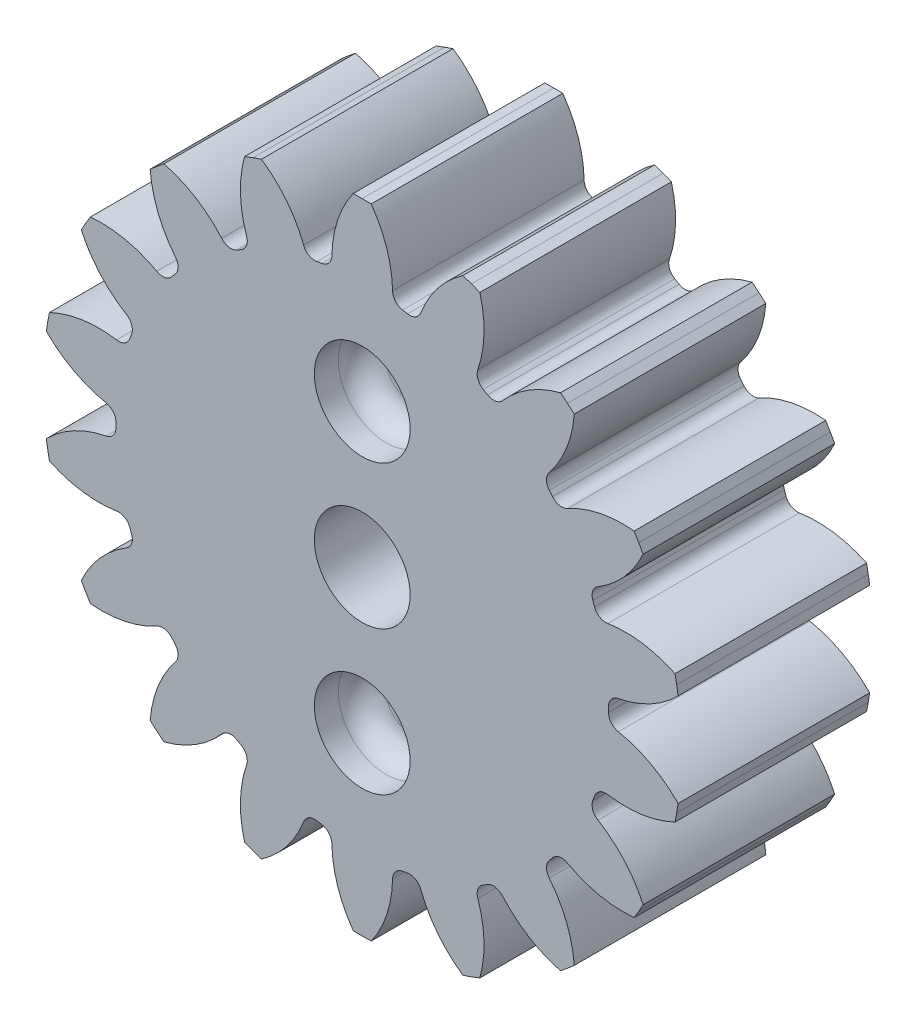
SolidWorks part; units mm, degrees
ref_plane "Front Plane" through (0, 0, 0) normal (0, 0, 1) x (1, 0, 0)
ref_plane "Top Plane" through (0, 0, 0) normal (0, 1, 0) x (1, 0, 0)
ref_plane "Right Plane" through (0, 0, 0) normal (1, 0, 0) x (0, 0, -1)
sketch "Sketch1" plane through (0, 0, 0) normal (0, 0, 1) x (1, 0, 0)
  line L0 (0, 42.3418) -> (0, -42.3418) construction
  line L1 (-42.3418, 0) -> (42.3418, 0) construction
  line L2 (0, 42.3418) -> (-1.1938, 42.325)
  line L3 (14.4817, 39.7883) -> (15.5978, 39.3642)
  line L4 (0, 42.3418) -> (1.1938, 42.325)
  line L5 (14.4817, 39.7883) -> (13.3542, 40.1808)
  line L6 (27.2168, 32.4357) -> (28.1205, 31.6554)
  line L7 (27.2168, 32.4357) -> (26.2915, 33.1902)
  line L8 (36.6691, 21.1709) -> (37.2514, 20.1286)
  line L9 (36.6691, 21.1709) -> (36.0576, 22.1963)
  line L10 (41.6985, 7.3526) -> (41.8893, 6.174)
  line L11 (41.6985, 7.3526) -> (41.4747, 8.5253)
  line L12 (41.6985, -7.3526) -> (41.4747, -8.5253)
  line L13 (41.6985, -7.3526) -> (41.8893, -6.174)
  line L14 (36.6691, -21.1709) -> (36.0576, -22.1963)
  line L15 (36.6691, -21.1709) -> (37.2514, -20.1286)
  line L16 (27.2168, -32.4357) -> (26.2915, -33.1902)
  line L17 (27.2168, -32.4357) -> (28.1205, -31.6554)
  line L18 (14.4817, -39.7883) -> (13.3542, -40.1808)
  line L19 (14.4817, -39.7883) -> (15.5978, -39.3642)
  line L20 (0, -42.3418) -> (-1.1938, -42.325)
  line L21 (0, -42.3418) -> (1.1938, -42.325)
  line L22 (-14.4817, -39.7883) -> (-15.5978, -39.3642)
  line L23 (-14.4817, -39.7883) -> (-13.3542, -40.1808)
  line L24 (-27.2168, -32.4357) -> (-28.1205, -31.6554)
  line L25 (-27.2168, -32.4357) -> (-26.2915, -33.1902)
  line L26 (-36.6691, -21.1709) -> (-37.2514, -20.1286)
  line L27 (-36.6691, -21.1709) -> (-36.0576, -22.1963)
  line L28 (-41.6985, -7.3526) -> (-41.8893, -6.174)
  line L29 (-41.6985, -7.3526) -> (-41.4747, -8.5253)
  line L30 (-41.6985, 7.3526) -> (-41.4747, 8.5253)
  line L31 (-41.6985, 7.3526) -> (-41.8893, 6.174)
  line L32 (-36.6691, 21.1709) -> (-36.0576, 22.1963)
  line L33 (-36.6691, 21.1709) -> (-37.2514, 20.1286)
  line L34 (-27.2168, 32.4357) -> (-26.2915, 33.1902)
  line L35 (-27.2168, 32.4357) -> (-28.1205, 31.6554)
  line L36 (-14.4817, 39.7883) -> (-13.3542, 40.1808)
  line L37 (-14.4817, 39.7883) -> (-15.5978, 39.3642)
  arc A0 (-36.0576, 22.1963) -> (-37.2514, 20.1286) centre (0, 0) ccw
  arc A2 (-16.0423, 28.4536) -> (-16.6204, 28.1198) centre (0, 0) ccw
  circle A3 centre (0, 0) radius 6.35
  arc A4 (4.0259, 33.778) -> (5.3431, 32.2244) centre (5.6007, 33.778) ccw
  arc A5 (-4.0259, 33.778) -> (-5.3431, 32.2244) centre (-5.6007, 33.778) cw
  arc A7 (4.0269, 33.7207) -> (1.1938, 42.325) centre (-11.211, 33.4718) ccw
  arc A8 (-4.0269, 33.7207) -> (-1.1938, 42.325) centre (11.211, 33.4718) cw
  arc A9 (7.7491, 33.0644) -> (13.3542, 40.1808) centre (21.983, 27.6188) cw
  arc A10 (7.7697, 33.1179) -> (6.0005, 32.1085) centre (6.2898, 33.6565) cw
  arc A11 (15.3172, 30.3098) -> (15.5978, 39.3642) centre (0.9131, 35.2876) ccw
  arc A12 (15.3359, 30.364) -> (16.0423, 28.4536) centre (16.8157, 29.8254) ccw
  arc A13 (18.5904, 28.42) -> (26.2915, 33.1902) centre (30.1034, 18.4346) cw
  arc A14 (18.6281, 28.4633) -> (16.6204, 28.1198) centre (17.4217, 29.4755) cw
  arc A15 (24.7601, 23.2431) -> (28.1205, 31.6554) centre (12.9271, 32.8472) ccw
  arc A16 (24.7961, 23.2877) -> (24.8065, 21.2509) centre (26.0025, 22.2754) ccw
  arc A17 (27.1895, 20.3478) -> (36.0576, 22.1963) centre (34.593, 7.0269) cw
  arc A18 (27.2397, 20.3755) -> (25.2356, 20.7395) centre (26.4523, 21.7394) cw
  arc A19 (31.2164, 13.3729) -> (37.2514, 20.1286) centre (23.3819, 26.4449) ccw
  arc A20 (31.2656, 13.4025) -> (30.5787, 11.485) centre (32.053, 12.0387) ccw
  arc A21 (32.5091, 9.8213) -> (41.4747, 8.5253) centre (34.9101, -5.2284) cw
  arc A22 (32.5658, 9.8302) -> (30.8071, 10.8576) centre (32.2923, 11.3811) cw
  arc A23 (33.9077, 1.8898) -> (41.8893, 6.174) centre (31.0165, 16.853) ccw
  arc A24 (33.964, 1.9008) -> (32.6627, 0.3338) centre (34.2374, 0.3499) ccw
  arc A25 (33.9077, -1.8898) -> (41.8893, -6.174) centre (31.0165, -16.853) cw
  arc A26 (33.964, -1.9008) -> (32.6627, -0.3338) centre (34.2374, -0.3499) cw
  arc A27 (32.5091, -9.8213) -> (41.4747, -8.5253) centre (34.9101, 5.2284) ccw
  arc A28 (32.5658, -9.8302) -> (30.8071, -10.8576) centre (32.2923, -11.3811) ccw
  arc A29 (31.2164, -13.3729) -> (37.2514, -20.1286) centre (23.3819, -26.4449) cw
  arc A30 (31.2656, -13.4025) -> (30.5787, -11.485) centre (32.053, -12.0387) cw
  arc A31 (27.1895, -20.3478) -> (36.0576, -22.1963) centre (34.593, -7.0269) ccw
  arc A32 (27.2397, -20.3755) -> (25.2356, -20.7395) centre (26.4523, -21.7394) ccw
  arc A33 (24.7601, -23.2431) -> (28.1205, -31.6554) centre (12.9271, -32.8472) cw
  arc A34 (24.7961, -23.2877) -> (24.8065, -21.2509) centre (26.0025, -22.2754) cw
  arc A35 (18.5904, -28.42) -> (26.2915, -33.1902) centre (30.1034, -18.4346) ccw
  arc A36 (18.6281, -28.4633) -> (16.6204, -28.1198) centre (17.4217, -29.4755) ccw
  arc A37 (15.3172, -30.3098) -> (15.5978, -39.3642) centre (0.9131, -35.2876) cw
  arc A38 (15.3359, -30.364) -> (16.0423, -28.4536) centre (16.8157, -29.8254) cw
  arc A39 (7.7491, -33.0644) -> (13.3542, -40.1808) centre (21.983, -27.6188) ccw
  arc A40 (7.7697, -33.1179) -> (6.0005, -32.1085) centre (6.2898, -33.6565) ccw
  arc A41 (4.0269, -33.7207) -> (1.1938, -42.325) centre (-11.211, -33.4718) cw
  arc A42 (4.0259, -33.778) -> (5.3431, -32.2244) centre (5.6007, -33.778) cw
  arc A43 (-4.0269, -33.7207) -> (-1.1938, -42.325) centre (11.211, -33.4718) ccw
  arc A44 (-4.0259, -33.778) -> (-5.3431, -32.2244) centre (-5.6007, -33.778) ccw
  arc A45 (-7.7491, -33.0644) -> (-13.3542, -40.1808) centre (-21.983, -27.6188) cw
  arc A46 (-7.7697, -33.1179) -> (-6.0005, -32.1085) centre (-6.2898, -33.6565) cw
  arc A47 (-15.3172, -30.3098) -> (-15.5978, -39.3642) centre (-0.9131, -35.2876) ccw
  arc A48 (-15.3359, -30.364) -> (-16.0423, -28.4536) centre (-16.8157, -29.8254) ccw
  arc A49 (-18.5904, -28.42) -> (-26.2915, -33.1902) centre (-30.1034, -18.4346) cw
  arc A50 (-18.6281, -28.4633) -> (-16.6204, -28.1198) centre (-17.4217, -29.4755) cw
  arc A51 (-24.7601, -23.2431) -> (-28.1205, -31.6554) centre (-12.9271, -32.8472) ccw
  arc A52 (-24.7961, -23.2877) -> (-24.8065, -21.2509) centre (-26.0025, -22.2754) ccw
  arc A53 (-27.1895, -20.3478) -> (-36.0576, -22.1963) centre (-34.593, -7.0269) cw
  arc A54 (-27.2397, -20.3755) -> (-25.2356, -20.7395) centre (-26.4523, -21.7394) cw
  arc A55 (-31.2164, -13.3729) -> (-37.2514, -20.1286) centre (-23.3819, -26.4449) ccw
  arc A56 (-31.2656, -13.4025) -> (-30.5787, -11.485) centre (-32.053, -12.0387) ccw
  arc A57 (-32.5091, -9.8213) -> (-41.4747, -8.5253) centre (-34.9101, 5.2284) cw
  arc A58 (-32.5658, -9.8302) -> (-30.8071, -10.8576) centre (-32.2923, -11.3811) cw
  arc A59 (-33.9077, -1.8898) -> (-41.8893, -6.174) centre (-31.0165, -16.853) ccw
  arc A60 (-33.964, -1.9008) -> (-32.6627, -0.3338) centre (-34.2374, -0.3499) ccw
  arc A61 (-33.9077, 1.8898) -> (-41.8893, 6.174) centre (-31.0165, 16.853) cw
  arc A62 (-33.964, 1.9008) -> (-32.6627, 0.3338) centre (-34.2374, 0.3499) cw
  arc A63 (-32.5091, 9.8213) -> (-41.4747, 8.5253) centre (-34.9101, -5.2284) ccw
  arc A64 (-32.5658, 9.8302) -> (-30.8071, 10.8576) centre (-32.2923, 11.3811) ccw
  arc A65 (-31.2164, 13.3729) -> (-37.2514, 20.1286) centre (-23.3819, 26.4449) cw
  arc A66 (-31.2656, 13.4025) -> (-30.5787, 11.485) centre (-32.053, 12.0387) cw
  arc A67 (-27.1895, 20.3478) -> (-36.0576, 22.1963) centre (-34.593, 7.0269) ccw
  arc A68 (-27.2397, 20.3755) -> (-25.2356, 20.7395) centre (-26.4523, 21.7394) ccw
  arc A69 (-24.7601, 23.2431) -> (-28.1205, 31.6554) centre (-12.9271, 32.8472) cw
  arc A70 (-24.7961, 23.2877) -> (-24.8065, 21.2509) centre (-26.0025, 22.2754) cw
  arc A71 (-18.5904, 28.42) -> (-26.2915, 33.1902) centre (-30.1034, 18.4346) ccw
  arc A72 (-18.6281, 28.4633) -> (-16.6204, 28.1198) centre (-17.4217, 29.4755) ccw
  arc A73 (-15.3172, 30.3098) -> (-15.5978, 39.3642) centre (-0.9131, 35.2876) cw
  arc A74 (-15.3359, 30.364) -> (-16.0423, 28.4536) centre (-16.8157, 29.8254) cw
  arc A75 (-7.7491, 33.0644) -> (-13.3542, 40.1808) centre (-21.983, 27.6188) ccw
  arc A76 (-7.7697, 33.1179) -> (-6.0005, 32.1085) centre (-6.2898, 33.6565) ccw
  arc A77 (-24.8065, 21.2509) -> (-25.2356, 20.7395) centre (0, 0) ccw
  arc A78 (-30.5787, 11.485) -> (-30.8071, 10.8576) centre (0, 0) ccw
  arc A79 (-5.3431, 32.2244) -> (-6.0005, 32.1085) centre (0, 0) ccw
  arc A80 (6.0005, 32.1085) -> (5.3431, 32.2244) centre (0, 0) ccw
  arc A81 (16.6204, 28.1198) -> (16.0423, 28.4536) centre (0, 0) ccw
  arc A82 (25.2356, 20.7395) -> (24.8065, 21.2509) centre (0, 0) ccw
  arc A83 (30.8071, 10.8576) -> (30.5787, 11.485) centre (0, 0) ccw
  arc A84 (32.6627, -0.3338) -> (32.6627, 0.3338) centre (0, 0) ccw
  arc A85 (30.5787, -11.485) -> (30.8071, -10.8576) centre (0, 0) ccw
  arc A86 (24.8065, -21.2509) -> (25.2356, -20.7395) centre (0, 0) ccw
  arc A87 (16.0423, -28.4536) -> (16.6204, -28.1198) centre (0, 0) ccw
  arc A88 (5.3431, -32.2244) -> (6.0005, -32.1085) centre (0, 0) ccw
  arc A89 (-6.0005, -32.1085) -> (-5.3431, -32.2244) centre (0, 0) ccw
  arc A90 (-16.6204, -28.1198) -> (-16.0423, -28.4536) centre (0, 0) ccw
  arc A91 (-25.2356, -20.7395) -> (-24.8065, -21.2509) centre (0, 0) ccw
  arc A92 (-30.8071, -10.8576) -> (-30.5787, -11.485) centre (0, 0) ccw
  arc A93 (-32.6627, 0.3338) -> (-32.6627, -0.3338) centre (0, 0) ccw
  arc A94 (-41.4747, 8.5253) -> (-41.8893, 6.174) centre (0, 0) ccw
  arc A95 (-41.8893, -6.174) -> (-41.4747, -8.5253) centre (0, 0) ccw
  arc A96 (-37.2514, -20.1286) -> (-36.0576, -22.1963) centre (0, 0) ccw
  arc A97 (-28.1205, -31.6554) -> (-26.2915, -33.1902) centre (0, 0) ccw
  arc A98 (-15.5978, -39.3642) -> (-13.3542, -40.1808) centre (0, 0) ccw
  arc A99 (-1.1938, -42.325) -> (1.1938, -42.325) centre (0, 0) ccw
  arc A100 (13.3542, -40.1808) -> (15.5978, -39.3642) centre (0, 0) ccw
  arc A101 (26.2915, -33.1902) -> (28.1205, -31.6554) centre (0, 0) ccw
  arc A102 (41.4747, -8.5253) -> (41.8893, -6.174) centre (0, 0) ccw
  arc A103 (41.8893, 6.174) -> (41.4747, 8.5253) centre (0, 0) ccw
  arc A104 (37.2514, 20.1286) -> (36.0576, 22.1963) centre (0, 0) ccw
  arc A105 (28.1205, 31.6554) -> (26.2915, 33.1902) centre (0, 0) ccw
  arc A106 (15.5978, 39.3642) -> (13.3542, 40.1808) centre (0, 0) ccw
  arc A107 (1.1938, 42.325) -> (-1.1938, 42.325) centre (0, 0) ccw
  arc A108 (-13.3542, 40.1808) -> (-15.5978, 39.3642) centre (0, 0) ccw
  arc A109 (-26.2915, 33.1902) -> (-28.1205, 31.6554) centre (0, 0) ccw
  point P245 (0, 0)
  dimension "D2" = 9.6774
  dimension "D4" = 12.7
  dimension "D6" = 1.5748
  dimension "D8" = 4.0269
  dimension "D5" = 4.0259
  dimension "D9" = 15.24
  dimension "D7" = 1.1938
  dimension "D10" = 18
extrude "Boss-Extrude1" add sketch "Sketch1" along normal blind 25.4 contours A62 A93 A60 A59 L28 L29 A57 A58 A92 A56 A55 L26 L27 A53 A54 A91 A52 A51 L24 L25 A49 A50 A90 A48 A47 L22 L23 A45 A46 A89 A44 A43 L20 L21 A41 A42 A88 A40 A39 L18
sketch "Sketch2" plane through (0, 0, 25.4) normal (0, 0, 1) x (1, 0, 0)
  line L0 (-25.4, 0) -> (25.4, 0) construction
  circle A0 centre (0, 0) radius 12.7
  circle A1 centre (0, 0) radius 25.4
  circle A2 centre (0, -19.05) radius 6.35
  circle A3 centre (0, 19.05) radius 6.35
  dimension "D1" = 25.4
  dimension "D2" = 50.8
extrude "Cut-Extrude1" cut sketch "Sketch2" against normal blind 6.35 contours A3 | A2 L0
sketch "Sketch3" plane through (0, 0, 0) normal (0, 0, -1) x (-1, 0, 0)
  line L0 (-25.4, 0) -> (25.4, 0) construction
  circle A0 centre (0, 0) radius 12.7
  circle A1 centre (0, 0) radius 25.4
  circle A2 centre (0, -19.05) radius 6.35
  circle A3 centre (0, 19.05) radius 6.35
  dimension "D1" = 25.4
  dimension "D2" = 50.8
extrude "Cut-Extrude2" cut sketch "Sketch3" against normal blind 6.35 contours A3 | A2 L0
fillet "Fillet1" radius 3.175 4 edges at (-6.35, -19.05, 6.35) (-6.35, 19.05, 6.35) (6.35, -19.05, 19.05) (6.35, 19.05, 19.05)
